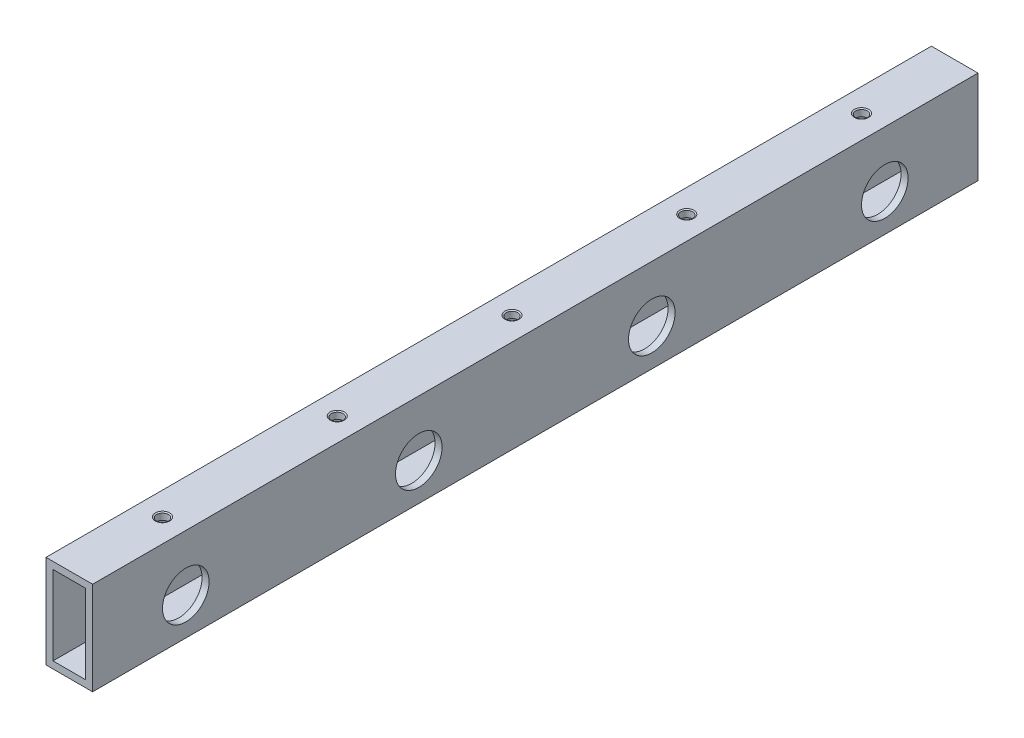
SolidWorks part; units mm, degrees
material "Д16Т ГОСТ 4784-74"
ref_plane "Спереди" through (0, 0, 0) normal (0, 0, 1) x (1, 0, 0)
ref_plane "Сверху" through (0, 0, 0) normal (0, 1, 0) x (1, 0, 0)
ref_plane "Справа" through (0, 0, 0) normal (1, 0, 0) x (0, 0, -1)
sketch "Эскиз1" plane through (0, 0, 0) normal (0, 0, 1) x (1, 0, 0)
  line L1 (0, 0) -> (10, 0)
  line L2 (0, 0) -> (0, 20)
  line L3 (0, 20) -> (10, 20)
  line L4 (10, 0) -> (10, 20)
  dimension "D1" = 20
  dimension "D2" = 10
extrude "Вытянуть-Тонкостенный1" add sketch "Эскиз1" along normal blind 190 thin thin type one direction reverse wall 1.5
hole_wizard "Отверстие обработанное метчиком M31" positions "Эскиз3" profile "Эскиз2" tap size "M3" standard "DIN"
sketch "Эскиз3" plane through (0, 20, 0) normal (0, 1, 0) x (-1, 0, 0)
  line L0 (-5, 0) -> (-5, 20)
  line L1 (-10, 0) -> (0, 0) construction
  line L3 (-5, 20) -> (-5, 57.5) construction
  point P0 (-5, 20)
  point P15 (-5, 57.5)
  point P16 (-5, 95)
  point P17 (-5, 132.5)
  point P18 (-5, 170)
  dimension "D1" = 20
  dimension "D3" = 37.5
  dimension "D2" = 5
sketch "Эскиз2" plane through (5, 20, 20) normal (1, 0, 0) x (0, 0, 1)
  line L0 (0, 0) -> (0, 9.2511)
  line L1 (0, 9.2511) -> (1.25, 8.5)
  line L2 (1.25, 8.5) -> (1.25, 0.1588)
  line L3 (1.25, 0.1588) -> (1.525, 0)
  line L5 (1.525, 0) -> (0, 0)
  line L6 (-1.25, 0.1588) -> (-1.525, 0) construction
  line L10 (0, 9.2511) -> (-1.25, 8.5) construction
  line L11 (0, -6.35) -> (0, 107.95) construction
  dimension "Диаметр сверла" = 2.5
  dimension "Глубина сверла" = 8.5
  dimension "Диаметр передней зенковки" = 3.05
  dimension "Угол передней зенковки" = 120
  dimension "Угол заточки сверла" = 118
cosmetic thread "Отверстие резьбы1" parameters "D1"=1.5, "D2"=3
cosmetic thread "Отверстие резьбы2" parameters "D1"=1.5, "D2"=3
cosmetic thread "Отверстие резьбы3" parameters "D1"=1.5, "D2"=3
cosmetic thread "Отверстие резьбы4" parameters "D1"=1.5, "D2"=3
cosmetic thread "Отверстие резьбы5" parameters "D1"=1.5, "D2"=3
hole_wizard "Отверстие2" positions "Эскиз7" profile "Эскиз6" legacy
sketch "Эскиз7" plane through (10, 0, 0) normal (1, 0, 0) x (0, 0, -1)
  line L0 (-95, 20) -> (-95, 0) construction
  line L1 (-190, 20) -> (0, 20) construction
  line L2 (-190, 0) -> (0, 0) construction
  point P0 (-170, 8)
  point P1 (-120, 8)
  point P14 (-70, 8)
  point P15 (-20, 8)
  dimension "D1" = 50
  dimension "D2" = 50
  dimension "D3" = 12
sketch "Эскиз6" plane through (10, 8, 170) normal (0, 1, 0) x (0, 0, -1)
  line L0 (0, 0) -> (0, 3)
  line L1 (0, 3) -> (5, 3)
  line L2 (5, 3) -> (5, 0)
  line L3 (5, 0) -> (0, 0)
  line L4 (0, 110) -> (0, -10) construction
  dimension "Диаметр" = 10
  dimension "Глубина" = 3
